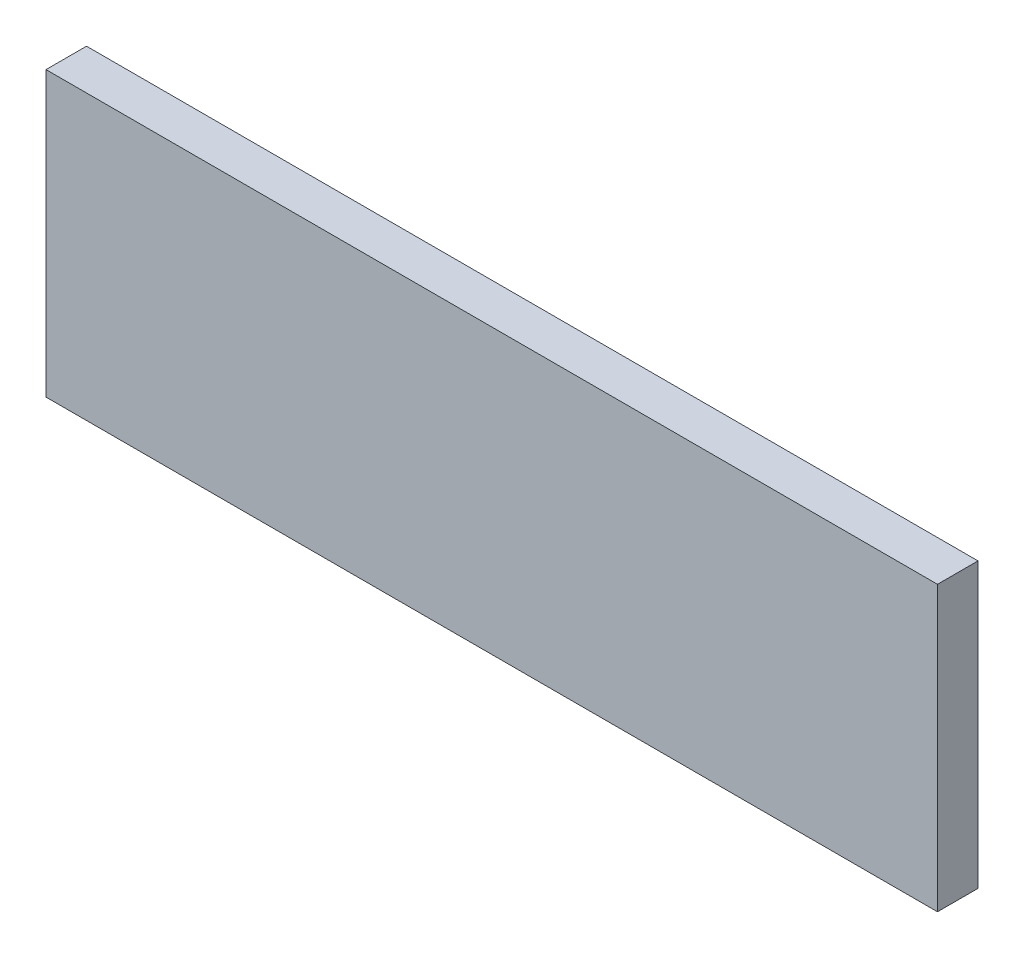
SolidWorks part; units mm, degrees
ref_plane "Plano frontal" through (0, 0, 0) normal (0, 0, 1) x (1, 0, 0)
ref_plane "Plano superior" through (0, 0, 0) normal (0, 1, 0) x (1, 0, 0)
ref_plane "Plano direito" through (0, 0, 0) normal (1, 0, 0) x (0, 0, -1)
sketch "Esboço1" plane through (0, 0, 0) normal (0, 0, 1) x (1, 0, 0)
  line L1 (-165, 52.5) -> (165, 52.5)
  line L2 (-165, 52.5) -> (-165, -52.5)
  line L3 (-165, -52.5) -> (165, -52.5)
  line L4 (165, 52.5) -> (165, -52.5)
  line L5 (-165, 52.5) -> (165, -52.5) construction
  line L6 (-165, -52.5) -> (165, 52.5) construction
  point P0 (0, 0)
  dimension "D1" = 330
  dimension "D2" = 105
extrude "Ressalto-extrusão1" add sketch "Esboço1" along normal blind 15
